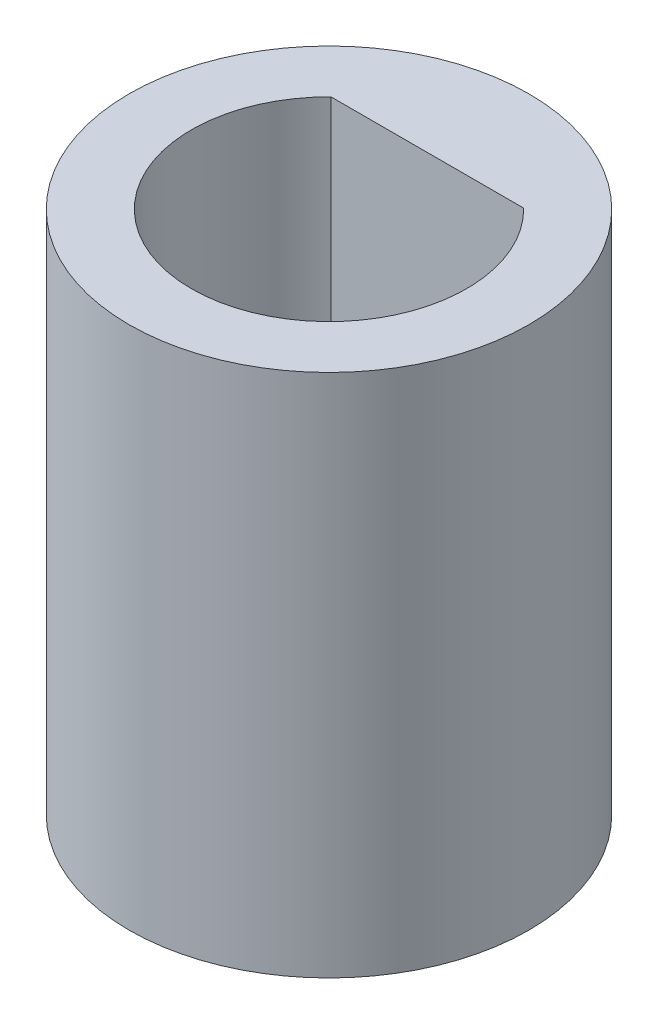
SolidWorks part; units mm, degrees
ref_plane "Front Plane" through (0, 0, 0) normal (0, 0, 1) x (1, 0, 0)
ref_plane "Top Plane" through (0, 0, 0) normal (0, 1, 0) x (1, 0, 0)
ref_plane "Right Plane" through (0, 0, 0) normal (1, 0, 0) x (0, 0, -1)
sketch "Sketch1" plane through (0, 0, 0) normal (0, 1, 0) x (1, 0, 0)
  line L0 (0, 0) -> (0, 4.985) construction
  line L1 (-1.4697, 1.5) -> (1.4697, 1.5)
  circle A0 centre (0, 0) radius 3.05
  arc A1 (-1.4697, 1.5) -> (1.4697, 1.5) centre (0, 0) ccw
  point P8 (0, 1.5)
  point P10 (0, -2.1)
  dimension "D1" = 6.1
  dimension "D2" = 4.2
  dimension "D3" = 3.6
extrude "Boss-Extrude1" add sketch "Sketch1" along normal blind 8
